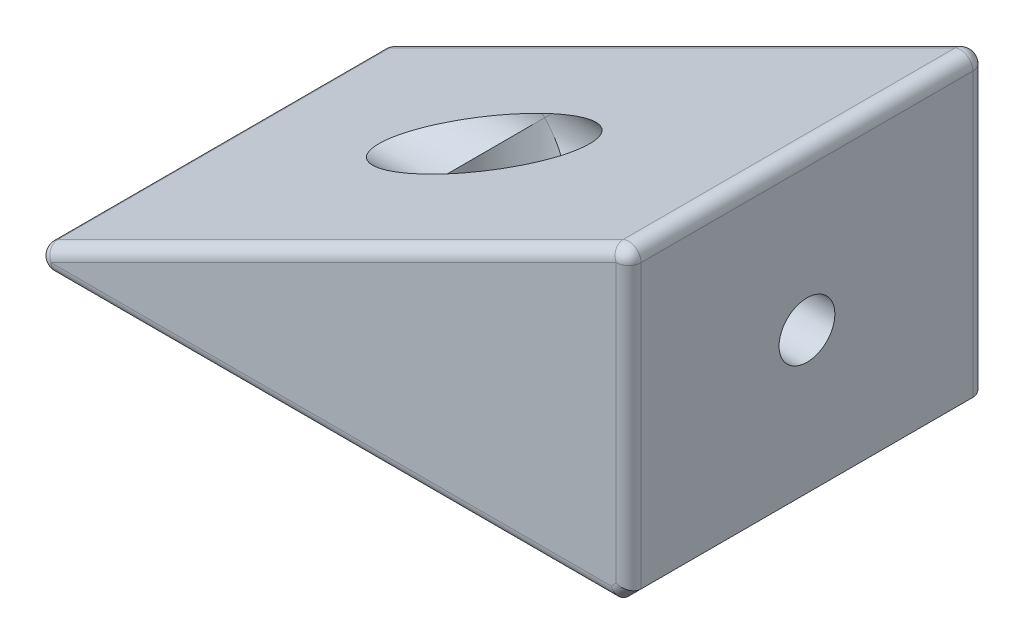
SolidWorks part; units mm, degrees
ref_plane "Front Plane" through (0, 0, 0) normal (0, 0, 1) x (1, 0, 0)
ref_plane "Top Plane" through (0, 0, 0) normal (0, 1, 0) x (1, 0, 0)
ref_plane "Right Plane" through (0, 0, 0) normal (1, 0, 0) x (0, 0, -1)
sketch "Sketch5" plane through (0, 0, 0) normal (0, 0, 1) x (1, 0, 0)
  line L0 (0, 0) -> (0, 25.4)
  line L1 (0, 25.4) -> (-50.8, 0)
  line L2 (-50.8, 0) -> (0, 0)
  dimension "D1" = 25.4
  dimension "D2" = 50.8
extrude "Boss-Extrude2" add sketch "Sketch5" along normal mid plane 28.75
hole_wizard "M4 Clearance Hole2" positions "Sketch9" profile "Sketch8" hole size "M4" standard "ANSI Metric" end condition up to next
sketch "Sketch9" plane through (0, 0, 0) normal (1, 0, 0) x (0, 0, -1)
  point P0 (0, 12.391)
sketch "Sketch8" plane through (0, 12.391, 0) normal (0, 1, 0) x (0, 0, -1)
  line L0 (0, 0) -> (0, 26.018)
  line L1 (0, 26.018) -> (2.25, 26.018)
  line L2 (2.25, 26.018) -> (2.25, 0)
  line L5 (2.25, 0) -> (0, 0)
  line L11 (0, -6.35) -> (0, 107.95) construction
  dimension "Thru Hole Dia." = 4.5
  dimension "Thru Hole Depth" = 26.018
sketch "Sketch10" plane through (0, 0, 0) normal (1, 0, 0) x (0, 0, -1)
  circle A0 centre (0, 12.391) radius 4.25
  dimension "D1" = 8.5
extrude "Cut-Extrude1" cut sketch "Sketch10" against normal blind 30 from offset 5 offset against normal yes
hole_wizard "M4 Clearance Hole3" positions "Sketch13" profile "Sketch12" hole size "M4" standard "ANSI Metric" end condition up to next
sketch "Sketch13" plane through (0, 0, 0) normal (0, -1, 0) x (-1, 0, 0)
  line L1 (50.8, 14.375) -> (0, 14.375) construction
  point P0 (25.4, 0)
  point P12 (25.4, 14.375)
sketch "Sketch12" plane through (-25.4, 0, 0) normal (1, 0, 0) x (0, 0, -1)
  line L0 (0, 0) -> (0, 8.141)
  line L1 (0, 8.141) -> (2.25, 8.141)
  line L2 (2.25, 8.141) -> (2.25, 0)
  line L5 (2.25, 0) -> (0, 0)
  line L11 (0, -6.35) -> (0, 107.95) construction
  dimension "Thru Hole Dia." = 4.5
  dimension "Thru Hole Depth" = 8.141
sketch "Sketch14" plane through (0, 0, 0) normal (0, -1, 0) x (1, 0, 0)
  circle A0 centre (-25.4, 0) radius 4.25
  dimension "D1" = 8.5
extrude "Cut-Extrude2" cut sketch "Sketch14" against normal blind 30 from offset 5 offset against normal yes
chamfer "Chamfer1" distance 1 angle 45 1 edges at (0, 0, 0)
fillet "Fillet2" radius 1 10 edges at (-50.8, 0, 0) (0, 13.2, -14.375) (-25.4, 12.7, -14.375) (-25.9, 0, -14.375) (-25.4, 12.7, 14.375) (0, 13.2, 14.375) (-25.9, 0, 14.375) (0, 25.4, 0) (-0.5, 0.5, -14.375) (-0.5, 0.5, 14.375)
